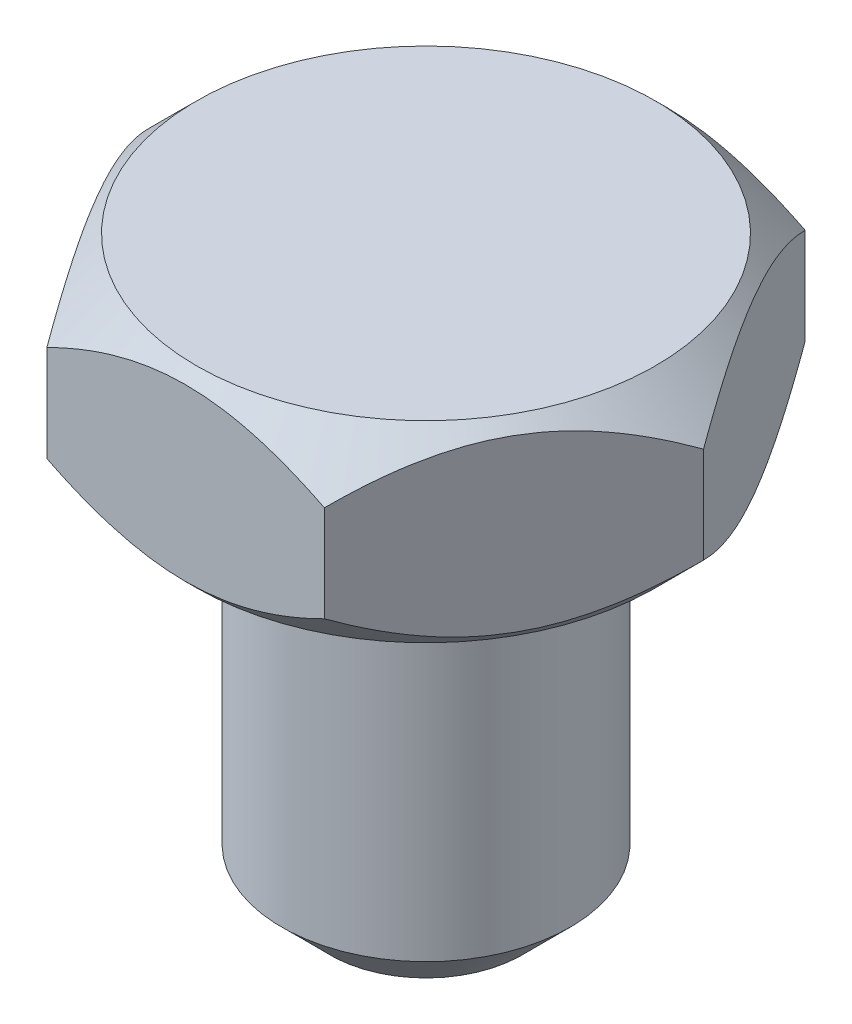
SolidWorks part; units mm, degrees
ref_plane "Спереди" through (0, 0, 0) normal (0, 0, 1) x (1, 0, 0)
ref_plane "Сверху" through (0, 0, 0) normal (0, 1, 0) x (1, 0, 0)
ref_plane "Справа" through (0, 0, 0) normal (1, 0, 0) x (0, 0, -1)
sketch "Эскиз1" plane through (0, 0, 0) normal (0, 1, 0) x (1, 0, 0)
  line L0 (-2.8868, 5) -> (2.8868, 5)
  line L1 (2.8868, 5) -> (5.7735, 0)
  line L2 (5.7735, 0) -> (2.8868, -5)
  line L3 (2.8868, -5) -> (-2.8868, -5)
  line L4 (-2.8868, -5) -> (-5.7735, 0)
  line L5 (-5.7735, 0) -> (-2.8868, 5)
  dimension "D1" = 5
  dimension "D2" = 120
  dimension "D3" = 120
  dimension "D4" = 120
  dimension "D5" = 120
  dimension "D6" = 5
  dimension "D7" = 5
  dimension "D8" = 5
  dimension "D9" = 5
  dimension "D10" = 5
extrude "Вытянуть1" add sketch "Эскиз1" against normal blind 4
sketch "Эскиз2" plane through (0, -4, 0) normal (0, -1, 0) x (1, 0, 0)
  circle A0 centre (0, 0) radius 3
  dimension "D1" = 6
extrude "Вытянуть2" add sketch "Эскиз2" along normal blind 8
chamfer "Фаска2" distance 1 angle 45 1 edges at (0, -12, -3)
ref_axis "Ось1" through (0, -4, 0) along (0, -1, 0)
ref_plane "Плоскость1" through (0, 0, 0) normal (0, 0, 1) x (1, 0, 0)
sketch "Эскиз3" plane through (0, 0, 0) normal (0, 0, 1) x (1, 0, 0)
  line L0 (-5.7735, -1) -> (-4.7735, 0)
  line L1 (-5.7735, -4) -> (-5.7735, 0) construction
  line L2 (-5.7735, 0) -> (-2.8868, 0) construction
  line L3 (-4.7735, 0) -> (-5.7735, 0)
  line L4 (-5.7735, 0) -> (-5.7735, -1)
  line L5 (-5.7735, -3) -> (-4.7735, -4)
  line L6 (-5.7735, -4) -> (-2.8868, -4) construction
  line L7 (-4.7735, -4) -> (-5.7735, -4)
  line L8 (-5.7735, -4) -> (-5.7735, -3)
  dimension "D1" = 1
  dimension "D2" = 1
  dimension "D3" = 1
  dimension "D4" = 1
revolve "Вырез-Повернуть1" cut sketch "Эскиз3" angle 360 about axis through (0, -4, 0) along (0, -1, 0)
